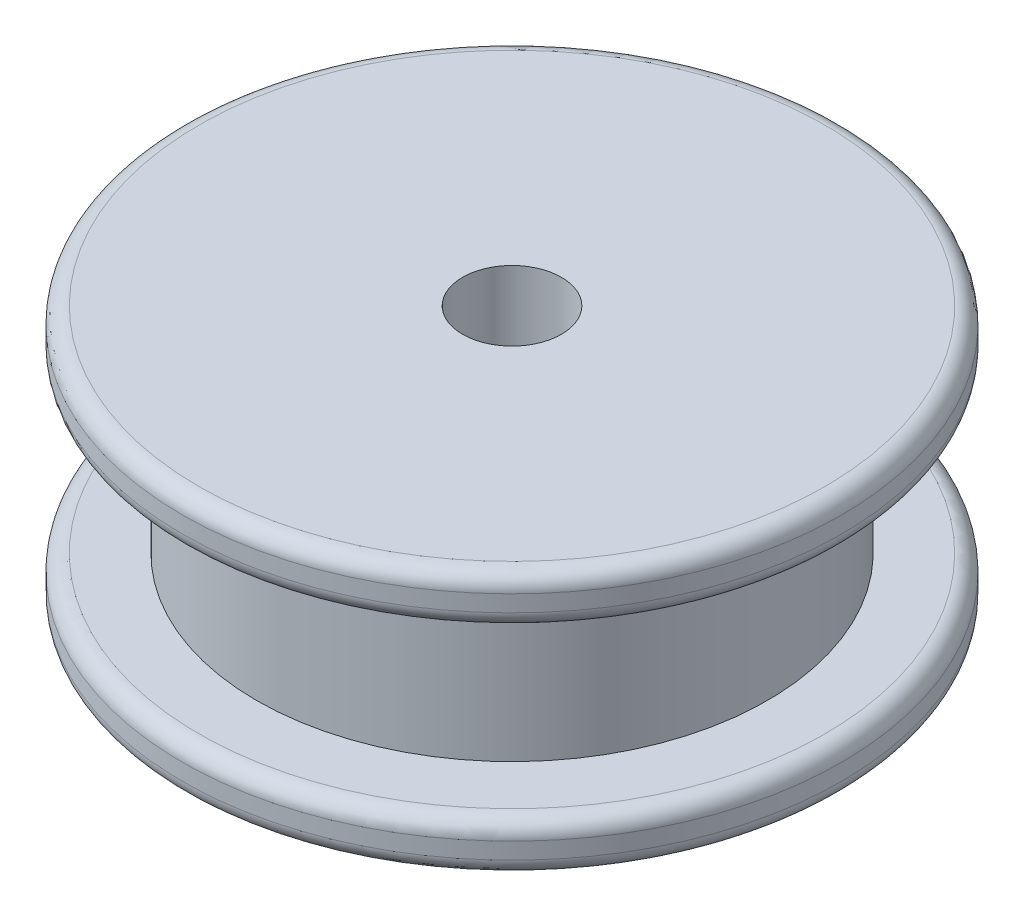
SolidWorks part; units mm, degrees
ref_plane "前视基准面" through (0, 0, 0) normal (0, 0, 1) x (1, 0, 0)
ref_plane "上视基准面" through (0, 0, 0) normal (0, 1, 0) x (1, 0, 0)
ref_plane "右视基准面" through (0, 0, 0) normal (1, 0, 0) x (0, 0, -1)
other "Configuration Table"
sketch "草图1" plane through (0, 0, 0) normal (0, 1, 0) x (1, 0, 0)
  circle A0 centre (0, 0) radius 15.5
  dimension "D1" = 31
extrude "凸台-拉伸1" add sketch "草图1" along normal blind 10
sketch "草图2" plane through (0, 10, 0) normal (0, 1, 0) x (1, 0, 0)
  circle A0 centre (0, 0) radius 20
  dimension "D1" = 40
extrude "凸台-拉伸2" add sketch "草图2" along normal blind 3
sketch "草图3" plane through (0, 0, 0) normal (0, -1, 0) x (1, 0, 0)
  circle A0 centre (0, 0) radius 20
  dimension "D1" = 40
extrude "凸台-拉伸3" add sketch "草图3" along normal blind 3
fillet "圆角2" radius 1 4 edges at (0, 0, -20) (0, -3, -20) (0, 10, 20) (0, 13, 20)
sketch "草图4" plane through (0, 13, 0) normal (0, 1, 0) x (1, 0, 0)
  circle A0 centre (0, 0) radius 3
extrude "切除-拉伸1" cut sketch "草图4" against normal through all
